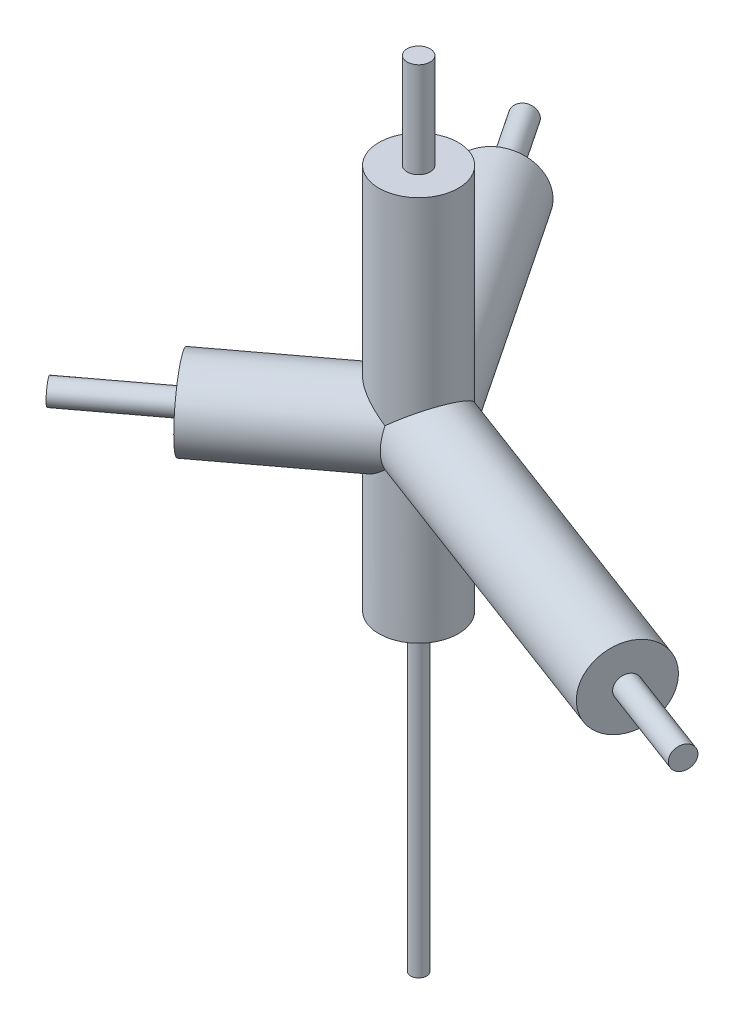
SolidWorks part; units mm, degrees
ref_plane "前视基准面" through (0, 0, 0) normal (0, 0, 1) x (1, 0, 0)
ref_plane "上视基准面" through (0, 0, 0) normal (0, 1, 0) x (1, 0, 0)
ref_plane "右视基准面" through (0, 0, 0) normal (1, 0, 0) x (0, 0, -1)
sketch "草图1" plane through (0, 0, 0) normal (0, 1, 0) x (1, 0, 0)
  line L0 (-26.6667, 40) -> (-26.6667, -20) construction
  line L1 (-26.6667, -20) -> (53.3333, -20) construction
  line L2 (-26.6667, 40) -> (53.3333, -20) construction
  line L3 (0, 0) -> (-26.6667, 40)
  line L4 (0, 0) -> (-26.6667, -20)
  line L5 (0, 0) -> (53.3333, -20)
  line L6 (0, 0) -> (41602.5147, 27735.0098) construction
  line L7 (0, 0) -> (30000, -40000) construction
  line L8 (0, 0) -> (17556.1721, 46816.4589) construction
  dimension "D1" = 60
  dimension "D2" = 80
  dimension "D3" = 20
  dimension "D4" = 26.6667
  dimension "D5" = 90
  dimension "D6" = 90
  dimension "D7" = 90
ref_plane "基准面1" through (0, 0, 0) normal (-0.8, 0, 0.6) x (0.6, 0, 0.8)
sketch "草图2" plane through (0, 0, 0) normal (-0.8, 0, 0.6) x (0.6, 0, 0.8)
  circle A0 centre (0, 0) radius 5
  dimension "D1" = 10
ref_plane "基准面2" through (0, 0, 0) normal (0.9363, 0, 0.3511) x (0.3511, 0, -0.9363)
ref_plane "基准面3" through (0, 0, 0) normal (0.5547, 0, 0.8321) x (0.8321, 0, -0.5547)
sketch "草图3" plane through (0, 0, 0) normal (0.9363, 0, 0.3511) x (0.3511, 0, -0.9363)
  circle A0 centre (0, 0) radius 5
  dimension "D1" = 10
sketch "草图4" plane through (0, 0, 0) normal (0.5547, 0, 0.8321) x (0.8321, 0, -0.5547)
  circle A0 centre (0, 0) radius 5
  dimension "D1" = 10
sweep "扫描1" add profiles "草图3" path "草图1"
sketch "草图5" plane through (0, 0, 0) normal (0, 1, 0) x (1, 0, 0)
  line L0 (0, 0) -> (-26.6667, 40)
sweep "扫描7" add profiles "草图4" path "草图5"
sketch "草图6" plane through (0, 0, 0) normal (0, 1, 0) x (1, 0, 0)
  line L0 (0, 0) -> (-26.6667, -20)
sweep "扫描8" add profiles "草图2" path "草图6"
sketch "草图7" plane through (-26.6667, 0, -40) normal (-0.5547, 0, -0.8321) x (-0.8321, 0, 0.5547)
  circle A0 centre (0, 0) radius 5
  circle A1 centre (0, 0) radius 1.45
  dimension "D1" = 10
  dimension "D2" = 2.9
extrude "切除-拉伸1" cut sketch "草图7" against normal blind 12
sketch "草图8" plane through (-26.6667, 0, 20) normal (-0.8, 0, 0.6) x (0.6, 0, 0.8)
  circle A0 centre (0, 0) radius 5
  circle A1 centre (0, 0) radius 1.45
  dimension "D1" = 10
  dimension "D2" = 2.9
extrude "切除-拉伸2" cut sketch "草图8" against normal blind 12
sketch "草图9" plane through (53.3333, 0, 20) normal (0.9363, 0, 0.3511) x (0.3511, 0, -0.9363)
  circle A0 centre (0, 0) radius 5
  circle A1 centre (0, 0) radius 1.45
  dimension "D1" = 10
  dimension "D2" = 2.9
extrude "切除-拉伸3" cut sketch "草图9" against normal blind 12
sketch "草图10" plane through (0, 0, 0) normal (0, 1, 0) x (1, 0, 0)
  circle A0 centre (0, 0) radius 5
  dimension "D1" = 10
extrude "凸台-拉伸1" add sketch "草图10" along normal blind 40 and the other way blind 60
sketch "草图12" plane through (0, 40, 0) normal (0, 1, 0) x (1, 0, 0)
  circle A0 centre (0, 0) radius 5
  circle A1 centre (0, 0) radius 1.45
  dimension "D1" = 10
  dimension "D2" = 2.9
extrude "切除-拉伸5" cut sketch "草图12" against normal blind 12
sketch "草图13" plane through (0, 0, 0) normal (1, 0, 0) x (0, 0, -1)
  line L0 (0, -1000) -> (0, 49000) construction
  line L1 (-5, -60) -> (5, -60) construction
  line L2 (-1, -20.025) -> (-1, -59.975)
  line L4 (-5, -60) -> (-1, -60)
  line L5 (-5, -60) -> (-5, -59.0176)
  line L6 (-5, -59.0176) -> (-1, -59.0176)
  line L7 (-1, -60) -> (-1, -59.0176)
  circle A0 centre (0, -40) radius 20
  dimension "D2" = 40
  dimension "D1" = 20
  dimension "D3" = 1
revolve "切除-旋转1" cut sketch "草图13" angle 360 about L0
